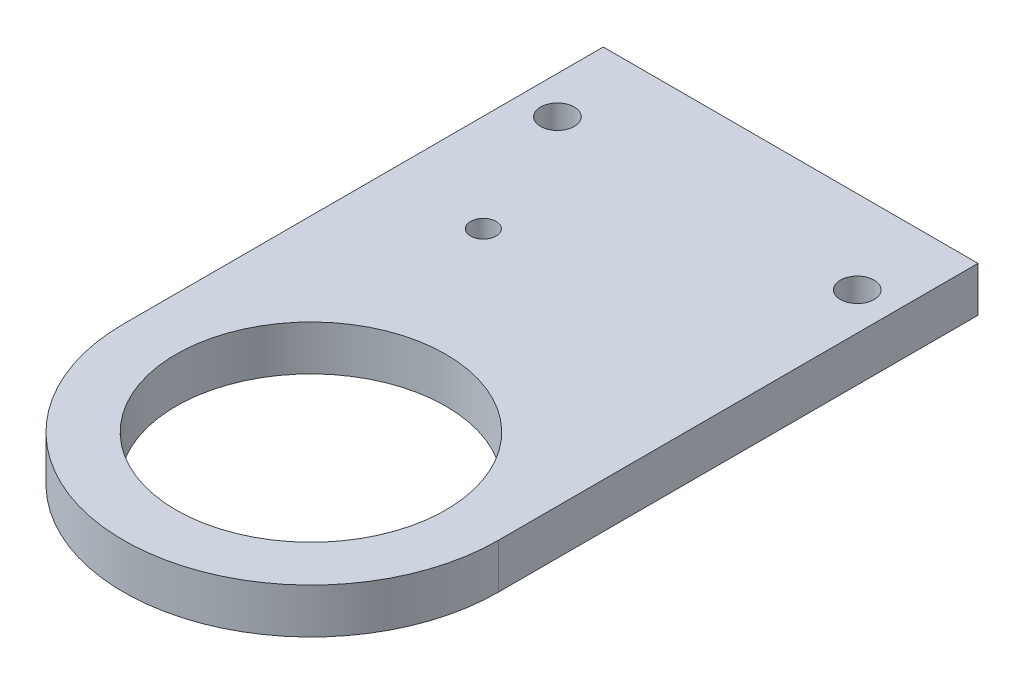
SolidWorks part; units mm, degrees
material "Aleación 6061"
ref_plane "Alzado" through (0, 0, 0) normal (0, 0, 1) x (1, 0, 0)
ref_plane "Planta" through (0, 0, 0) normal (0, 1, 0) x (1, 0, 0)
ref_plane "Vista lateral" through (0, 0, 0) normal (1, 0, 0) x (0, 0, -1)
sketch "Sk_Pared" plane through (0, 0, 0) normal (0, 1, 0) x (1, 0, 0)
  line L1 (-25, -490) -> (25, -490)
  line L2 (-25, -490) -> (-25, -426)
  line L3 (-25, -426) -> (25, -426)
  line L4 (25, -490) -> (25, -426)
  line L5 (-25, -490) -> (25, -426) construction
  line L6 (-25, -426) -> (25, -490) construction
  point P0 (0, -458)
  dimension "D1" = 50
  dimension "D2" = 64
  dimension "D3" = 458
extrude "Pared" add sketch "Sk_Pared" along normal blind 6 from offset 21.5
sketch "Sk_Cabeza" plane through (0, 0, 0) normal (0, 1, 0) x (1, 0, 0)
  circle A0 centre (0, -490) radius 25
  dimension "D1" = 50
  dimension "D2" = 490
extrude "Cabeza" add sketch "Sk_Cabeza" along normal blind 6 from offset 21.5
sketch "Sk_Paso_cubo_J5" plane through (0, 0, 0) normal (0, 1, 0) x (1, 0, 0)
  circle A0 centre (0, -490) radius 18
  dimension "D1" = 36
  dimension "D2" = 490
extrude "Paso_cubo_J5" cut sketch "Sk_Paso_cubo_J5" along normal blind 6 from offset 21.5
sketch "Sk_Pasantes_M4_angulos" plane through (0, 0, 0) normal (0, 1, 0) x (1, 0, 0)
  circle A0 centre (-20, -437.11) radius 2.25
  circle A1 centre (20, -437.11) radius 2.25
  dimension "D1" = 4.5
  dimension "D4" = 4.5
  dimension "D2" = 20
  dimension "D3" = 437.11
  dimension "D5" = 20
  dimension "D6" = 437.11
extrude "Pasantes_M4_angulos" cut sketch "Sk_Pasantes_M4_angulos" along normal blind 6 from offset 21.5
sketch "Sk_Pasante_M3_cincho" plane through (0, 0, 0) normal (0, 1, 0) x (1, 0, 0)
  circle A0 centre (-12, -455) radius 1.7
  dimension "D1" = 3.4
  dimension "D2" = 12
  dimension "D3" = 455
extrude "Pasante_M3_cincho" cut sketch "Sk_Pasante_M3_cincho" along normal blind 6 from offset 21.5
